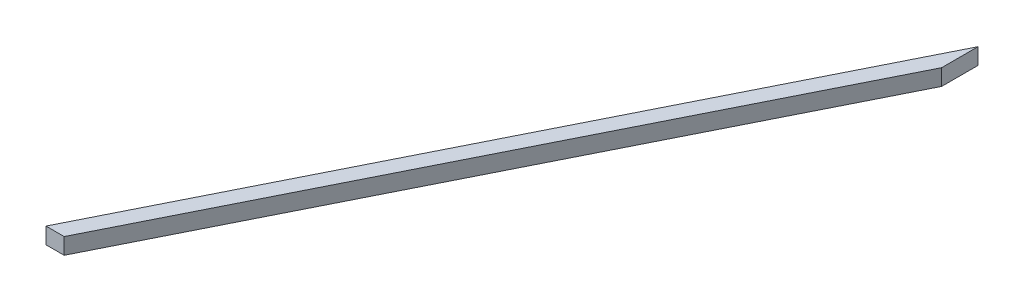
SolidWorks part; units mm, degrees
ref_plane "Front Plane" through (0, 0, 0) normal (0, 0, 1) x (1, 0, 0)
ref_plane "Top Plane" through (0, 0, 0) normal (0, 1, 0) x (1, 0, 0)
ref_plane "Right Plane" through (0, 0, 0) normal (1, 0, 0) x (0, 0, -1)
sketch "Sketch1" plane through (0, 0, 0) normal (0, 1, 0) x (1, 0, 0)
  line L1 (-130.2152, 830.4835) -> (-587.4152, -83.9165)
  line L3 (-587.4152, -83.9165) -> (-130.2152, 830.4835)
  line L6 (-610.1336, -72.5572) -> (-152.9336, 841.8428)
  line L7 (-587.4152, -83.9165) -> (-615.8133, -83.9165)
  line L8 (-130.2152, 830.4835) -> (-130.2152, 887.2797)
  line L9 (-152.9336, 841.8428) -> (-615.8133, -83.9165)
  line L10 (-615.8133, -83.9165) -> (-130.2152, 887.2797)
  dimension "D3" = 25.4
extrude "Boss-Extrude1" add sketch "Sketch1" along normal blind 25.4 contours L10 L6 L9 L7 L1 L8
